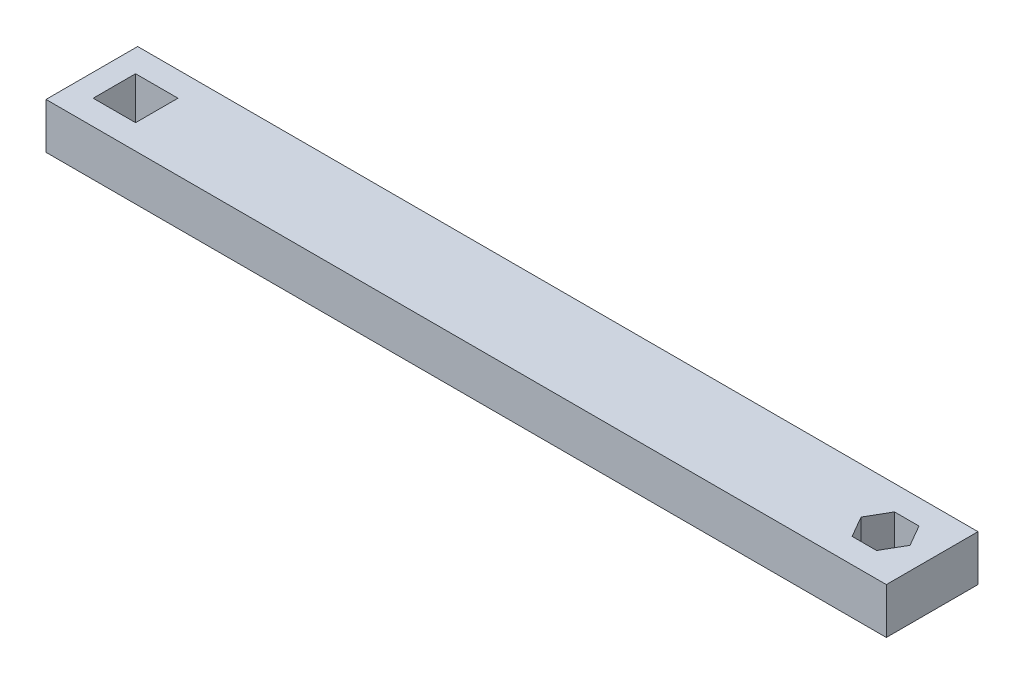
SolidWorks part; units mm, degrees
ref_plane "Płaszczyzna przednia" through (0, 0, 0) normal (0, 0, 1) x (1, 0, 0)
ref_plane "Płaszczyzna górna" through (0, 0, 0) normal (0, 1, 0) x (1, 0, 0)
ref_plane "Płaszczyzna prawa" through (0, 0, 0) normal (1, 0, 0) x (0, 0, -1)
sketch "Szkic1" plane through (0, 0, 0) normal (0, 1, 0) x (1, 0, 0)
  line L0 (0, -84.2413) -> (0, -96.2413)
  line L1 (0, -84.2413) -> (110, -84.2413)
  line L2 (0, -96.2413) -> (110, -96.2413)
  line L3 (110, -84.2413) -> (110, -96.2413)
  dimension "D1" = 12
  dimension "D2" = 110
extrude "Dodanie-wyciągnięcie1" add sketch "Szkic1" along normal blind 6
sketch "Szkic2" plane through (0, 6, 0) normal (0, 1, 0) x (1, 0, 0)
  line L0 (2.95, -87.4663) -> (8.5, -87.4663)
  line L1 (2.95, -87.4663) -> (2.95, -93.0163)
  line L2 (8.5, -87.4663) -> (8.5, -93.0163)
  line L3 (2.95, -93.0163) -> (8.5, -93.0163)
  line L5 (0, -96.2413) -> (110, -96.2413) construction
  line L6 (0, -84.2413) -> (0, -96.2413) construction
  point P6 (2.95, -90.2413)
  dimension "D1" = 6
  dimension "D2" = 5.55
  dimension "D3" = 5.55
  dimension "D4" = 8.5
extrude "Wytnij-wyciągnięcie1" cut sketch "Szkic2" against normal blind 6
sketch "Szkic3" plane through (0, 6, 0) normal (0, 1, 0) x (1, 0, 0)
  line L0 (0, -96.2413) -> (110, -96.2413) construction
  line L1 (102.2957, -93.0163) -> (105.5, -93.0163)
  line L2 (105.5, -93.0163) -> (107.1021, -90.2413)
  line L3 (107.1021, -90.2413) -> (105.5, -87.4663)
  line L4 (105.5, -87.4663) -> (102.2957, -87.4663)
  line L5 (102.2957, -87.4663) -> (100.6936, -90.2413)
  line L6 (100.6936, -90.2413) -> (102.2957, -93.0163)
  line L7 (110, -96.2413) -> (110, -84.2413) construction
  circle A0 centre (103.8979, -90.2413) radius 2.775 construction
  dimension "D3" = 6
  dimension "D1" = 0
  dimension "D2" = 4.5
extrude "Wytnij-wyciągnięcie2" cut sketch "Szkic3" against normal blind 6
